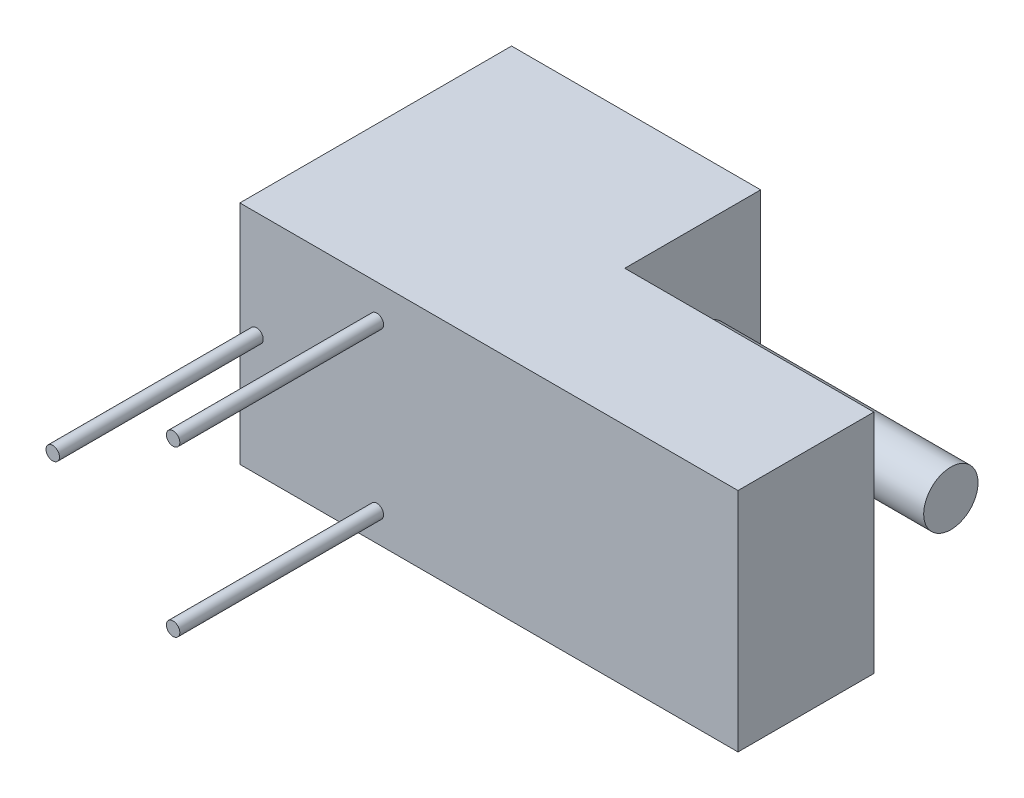
SolidWorks part; units mm, degrees
ref_plane "前视" through (0, 0, 0) normal (0, 0, 1) x (1, 0, 0)
ref_plane "上视" through (0, 0, 0) normal (0, 1, 0) x (1, 0, 0)
ref_plane "右视" through (0, 0, 0) normal (1, 0, 0) x (0, 0, -1)
sketch "草图1" plane through (0, 0, 0) normal (0, 0, 1) x (1, 0, 0)
  line L0 (0, 94.1326) -> (0, -87.3375) construction
  line L1 (-118.5152, 0) -> (112.5195, 0) construction
  line L3 (-5.5, 2.5) -> (5.5, 2.5)
  line L4 (-5.5, 2.5) -> (-5.5, -2.5)
  line L5 (-5.5, -2.5) -> (5.5, -2.5)
  line L6 (5.5, 2.5) -> (5.5, -2.5)
  dimension "D1" = 5
  dimension "D2" = 11
extrude "拉伸2" add sketch "草图1" along normal blind 6
sketch "草图2" plane through (0, 2.5, 0) normal (0, 1, 0) x (-1, 0, 0)
  line L0 (-7.6848, 3) -> (0, 3)
  line L4 (0, 3) -> (0, -1.8172)
extrude "切除-拉伸2" cut sketch "草图2" against normal through all flip side to cut
sketch "草图3" plane through (0, 0, 0) normal (1, 0, 0) x (0, 0, -1)
  line L0 (-6, 0) -> (-0.7, 0) construction
  line L1 (-6, -2.5) -> (-6, 2.5) construction
  circle A0 centre (-1.3, 0) radius 0.6
  dimension "D2" = 1.2
  dimension "D1" = 5.3
extrude "拉伸3" add sketch "草图3" along normal up to surface (5.5 mm away) up to face at (5.5, 0, 4.5)
sketch "草图4" plane through (0, 0, 6) normal (0, 0, 1) x (1, 0, 0)
  circle A0 centre (-5.1319, 0.1486) radius 0.1486
  circle A1 centre (-2.4742, 1.7573) radius 0.1486
  circle A2 centre (-2.4742, -1.8797) radius 0.1486
extrude "拉伸4" add sketch "草图4" along normal blind 4.5
